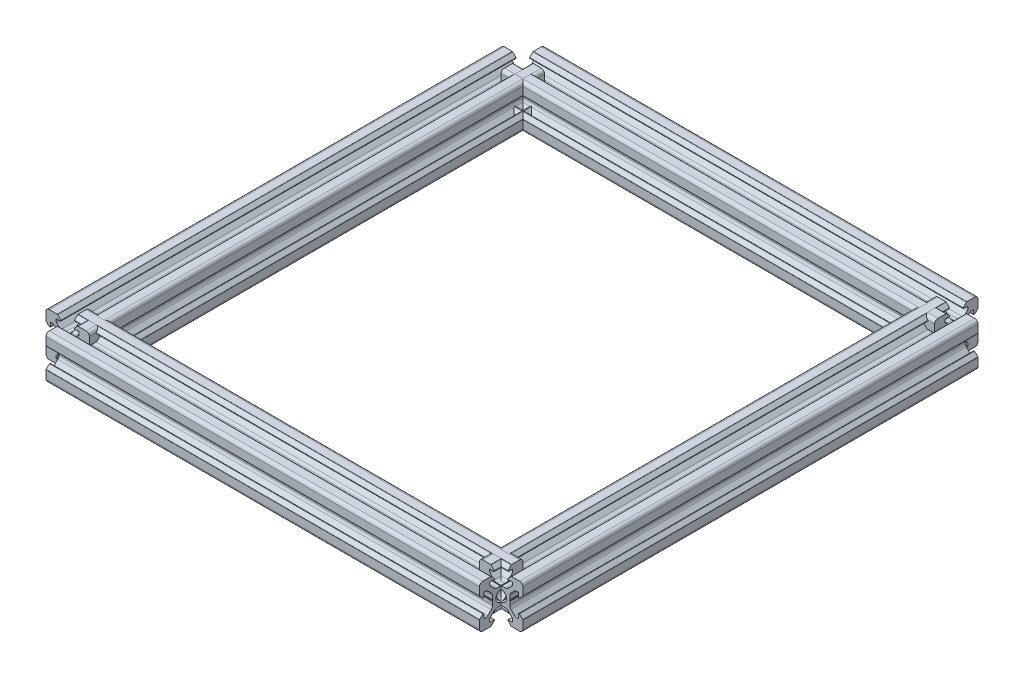
SolidWorks part; units mm, degrees
material "6061 Alloy"
ref_plane "Front Plane" through (0, 0, 0) normal (0, 0, 1) x (1, 0, 0)
ref_plane "Top Plane" through (0, 0, 0) normal (0, 1, 0) x (1, 0, 0)
ref_plane "Right Plane" through (0, 0, 0) normal (1, 0, 0) x (0, 0, -1)
sketch "Sketch1" plane through (0, 0, 0) normal (0, 1, 0) x (1, 0, 0)
  line L1 (-100, 105) -> (100, 105)
  line L2 (-100, 105) -> (-100, -105)
  line L3 (-100, -105) -> (100, -105)
  line L4 (100, 105) -> (100, -105)
  line L5 (-100, 105) -> (100, -105) construction
  line L6 (-100, -105) -> (100, 105) construction
  point P0 (0, 0)
  dimension "D1" = 200
  dimension "D2" = 210
other "Profile_20х20 20X20(1)"
ref_plane "Plane2" through (-100, 0, -105) normal (0, 0, 1) x (1, 0, 0)
sketch "Сечение" plane through (-100, 0, -105) normal (0, 0, 1) x (1, 0, 0)
  line L0 (-4, 1.8988) -> (-4, 0.3377)
  line L1 (-3.9452, 0.1815) -> (-3.8, 0)
  line L2 (-3.8, 0) -> (-3.9452, -0.1815)
  line L3 (-4, -0.3377) -> (-4, -1.8988)
  line L4 (-4.5858, -3.313) -> (-6.2799, -5.0071)
  line L5 (-6.987, -5.3) -> (-7.8, -5.3)
  line L6 (-8, -5.1) -> (-8, -3.33)
  line L7 (-8.4268, -3.1532) -> (-9.9268, -4.6532)
  line L8 (-10, -4.83) -> (-10, -8.5)
  line L9 (-8.5, -10) -> (-4.83, -10)
  line L10 (-4.6532, -9.9268) -> (-3.1532, -8.4268)
  line L11 (-3.33, -8) -> (-5.1, -8)
  line L12 (-5.3, -7.8) -> (-5.3, -6.987)
  line L13 (-5.0071, -6.2799) -> (-3.313, -4.5858)
  line L14 (-1.8988, -4) -> (-0.3377, -4)
  line L15 (-0.1815, -3.9452) -> (0, -3.8)
  line L16 (0, -3.8) -> (0.1815, -3.9452)
  line L17 (0.3377, -4) -> (1.8988, -4)
  line L18 (3.313, -4.5858) -> (5.0071, -6.2799)
  line L19 (5.3, -6.987) -> (5.3, -7.8)
  line L20 (5.1, -8) -> (3.33, -8)
  line L21 (3.1532, -8.4268) -> (4.6532, -9.9268)
  line L22 (4.83, -10) -> (8.5, -10)
  line L23 (10, -8.5) -> (10, -4.83)
  line L24 (9.9268, -4.6532) -> (8.4268, -3.1532)
  line L25 (8, -3.33) -> (8, -5.1)
  line L26 (7.8, -5.3) -> (6.987, -5.3)
  line L27 (6.2799, -5.0071) -> (4.5858, -3.313)
  line L28 (4, -1.8988) -> (4, -0.3377)
  line L29 (3.9452, -0.1815) -> (3.8, 0)
  line L30 (3.8, 0) -> (3.9452, 0.1815)
  line L31 (4, 0.3377) -> (4, 1.8988)
  line L32 (4.5858, 3.313) -> (6.2799, 5.0071)
  line L33 (6.987, 5.3) -> (7.8, 5.3)
  line L34 (8, 5.1) -> (8, 3.33)
  line L35 (8.4268, 3.1532) -> (9.9268, 4.6532)
  line L36 (10, 4.83) -> (10, 8.5)
  line L37 (8.5, 10) -> (4.83, 10)
  line L38 (4.6532, 9.9268) -> (3.1532, 8.4268)
  line L39 (3.33, 8) -> (5.1, 8)
  line L40 (5.3, 7.8) -> (5.3, 6.987)
  line L41 (5.0071, 6.2799) -> (3.313, 4.5858)
  line L42 (1.8988, 4) -> (0.3377, 4)
  line L43 (0.1815, 3.9452) -> (0, 3.8)
  line L44 (0, 3.8) -> (-0.1815, 3.9452)
  line L45 (-0.3377, 4) -> (-1.8988, 4)
  line L46 (-3.313, 4.5858) -> (-5.0071, 6.2799)
  line L47 (-5.3, 6.987) -> (-5.3, 7.8)
  line L48 (-5.1, 8) -> (-3.33, 8)
  line L49 (-3.1532, 8.4268) -> (-4.6532, 9.9268)
  line L50 (-4.83, 10) -> (-8.5, 10)
  line L51 (-10, 8.5) -> (-10, 4.83)
  line L52 (-9.9268, 4.6532) -> (-8.4268, 3.1532)
  line L53 (-8, 3.33) -> (-8, 5.1)
  line L54 (-7.8, 5.3) -> (-6.987, 5.3)
  line L55 (-6.2799, 5.0071) -> (-4.5858, 3.313)
  circle A0 centre (0, 0) radius 2.5
  arc A1 (-4, 0.3377) -> (-3.9452, 0.1815) centre (-3.75, 0.3377) ccw
  arc A2 (-3.9452, -0.1815) -> (-4, -0.3377) centre (-3.75, -0.3377) ccw
  arc A3 (-4, -1.8988) -> (-4.5858, -3.313) centre (-6, -1.8988) cw
  arc A4 (-6.2799, -5.0071) -> (-6.987, -5.3) centre (-6.987, -4.3) cw
  arc A5 (-7.8, -5.3) -> (-8, -5.1) centre (-7.8, -5.1) cw
  arc A6 (-8, -3.33) -> (-8.4268, -3.1532) centre (-8.25, -3.33) ccw
  arc A7 (-9.9268, -4.6532) -> (-10, -4.83) centre (-9.75, -4.83) ccw
  arc A8 (-10, -8.5) -> (-8.5, -10) centre (-8.5, -8.5) ccw
  arc A9 (-4.83, -10) -> (-4.6532, -9.9268) centre (-4.83, -9.75) ccw
  arc A10 (-3.1532, -8.4268) -> (-3.33, -8) centre (-3.33, -8.25) ccw
  arc A11 (-5.1, -8) -> (-5.3, -7.8) centre (-5.1, -7.8) cw
  arc A12 (-5.3, -6.987) -> (-5.0071, -6.2799) centre (-4.3, -6.987) cw
  arc A13 (-3.313, -4.5858) -> (-1.8988, -4) centre (-1.8988, -6) cw
  arc A14 (-0.3377, -4) -> (-0.1815, -3.9452) centre (-0.3377, -3.75) ccw
  arc A15 (0.1815, -3.9452) -> (0.3377, -4) centre (0.3377, -3.75) ccw
  arc A16 (1.8988, -4) -> (3.313, -4.5858) centre (1.8988, -6) cw
  arc A17 (5.0071, -6.2799) -> (5.3, -6.987) centre (4.3, -6.987) cw
  arc A18 (5.3, -7.8) -> (5.1, -8) centre (5.1, -7.8) cw
  arc A19 (3.33, -8) -> (3.1532, -8.4268) centre (3.33, -8.25) ccw
  arc A20 (4.6532, -9.9268) -> (4.83, -10) centre (4.83, -9.75) ccw
  arc A21 (8.5, -10) -> (10, -8.5) centre (8.5, -8.5) ccw
  arc A22 (10, -4.83) -> (9.9268, -4.6532) centre (9.75, -4.83) ccw
  arc A23 (8.4268, -3.1532) -> (8, -3.33) centre (8.25, -3.33) ccw
  arc A24 (8, -5.1) -> (7.8, -5.3) centre (7.8, -5.1) cw
  arc A25 (6.987, -5.3) -> (6.2799, -5.0071) centre (6.987, -4.3) cw
  arc A26 (4.5858, -3.313) -> (4, -1.8988) centre (6, -1.8988) cw
  arc A27 (4, -0.3377) -> (3.9452, -0.1815) centre (3.75, -0.3377) ccw
  arc A28 (3.9452, 0.1815) -> (4, 0.3377) centre (3.75, 0.3377) ccw
  arc A29 (4, 1.8988) -> (4.5858, 3.313) centre (6, 1.8988) cw
  arc A30 (6.2799, 5.0071) -> (6.987, 5.3) centre (6.987, 4.3) cw
  arc A31 (7.8, 5.3) -> (8, 5.1) centre (7.8, 5.1) cw
  arc A32 (8, 3.33) -> (8.4268, 3.1532) centre (8.25, 3.33) ccw
  arc A33 (9.9268, 4.6532) -> (10, 4.83) centre (9.75, 4.83) ccw
  arc A34 (10, 8.5) -> (8.5, 10) centre (8.5, 8.5) ccw
  arc A35 (4.83, 10) -> (4.6532, 9.9268) centre (4.83, 9.75) ccw
  arc A36 (3.1532, 8.4268) -> (3.33, 8) centre (3.33, 8.25) ccw
  arc A37 (5.1, 8) -> (5.3, 7.8) centre (5.1, 7.8) cw
  arc A38 (5.3, 6.987) -> (5.0071, 6.2799) centre (4.3, 6.987) cw
  arc A39 (3.313, 4.5858) -> (1.8988, 4) centre (1.8988, 6) cw
  arc A40 (0.3377, 4) -> (0.1815, 3.9452) centre (0.3377, 3.75) ccw
  arc A41 (-0.1815, 3.9452) -> (-0.3377, 4) centre (-0.3377, 3.75) ccw
  arc A42 (-1.8988, 4) -> (-3.313, 4.5858) centre (-1.8988, 6) cw
  arc A43 (-5.0071, 6.2799) -> (-5.3, 6.987) centre (-4.3, 6.987) cw
  arc A44 (-5.3, 7.8) -> (-5.1, 8) centre (-5.1, 7.8) cw
  arc A45 (-3.33, 8) -> (-3.1532, 8.4268) centre (-3.33, 8.25) ccw
  arc A46 (-4.6532, 9.9268) -> (-4.83, 10) centre (-4.83, 9.75) ccw
  arc A47 (-8.5, 10) -> (-10, 8.5) centre (-8.5, 8.5) ccw
  arc A48 (-10, 4.83) -> (-9.9268, 4.6532) centre (-9.75, 4.83) ccw
  arc A49 (-8.4268, 3.1532) -> (-8, 3.33) centre (-8.25, 3.33) ccw
  arc A50 (-8, 5.1) -> (-7.8, 5.3) centre (-7.8, 5.1) cw
  arc A51 (-6.987, 5.3) -> (-6.2799, 5.0071) centre (-6.987, 4.3) cw
  arc A52 (-4.5858, 3.313) -> (-4, 1.8988) centre (-6, 1.8988) cw
  point P162 (0, 0)
other "Profile_20х20 20X20(2)"
ref_plane "Plane4" through (-100, 0, 105) normal (1, 0, 0) x (0, 0, -1)
sketch "Сечение1" plane through (-100, 0, 105) normal (1, 0, 0) x (0, 0, -1)
  line L0 (-4, 1.8988) -> (-4, 0.3377)
  line L1 (-3.9452, 0.1815) -> (-3.8, 0)
  line L2 (-3.8, 0) -> (-3.9452, -0.1815)
  line L3 (-4, -0.3377) -> (-4, -1.8988)
  line L4 (-4.5858, -3.313) -> (-6.2799, -5.0071)
  line L5 (-6.987, -5.3) -> (-7.8, -5.3)
  line L6 (-8, -5.1) -> (-8, -3.33)
  line L7 (-8.4268, -3.1532) -> (-9.9268, -4.6532)
  line L8 (-10, -4.83) -> (-10, -8.5)
  line L9 (-8.5, -10) -> (-4.83, -10)
  line L10 (-4.6532, -9.9268) -> (-3.1532, -8.4268)
  line L11 (-3.33, -8) -> (-5.1, -8)
  line L12 (-5.3, -7.8) -> (-5.3, -6.987)
  line L13 (-5.0071, -6.2799) -> (-3.313, -4.5858)
  line L14 (-1.8988, -4) -> (-0.3377, -4)
  line L15 (-0.1815, -3.9452) -> (0, -3.8)
  line L16 (0, -3.8) -> (0.1815, -3.9452)
  line L17 (0.3377, -4) -> (1.8988, -4)
  line L18 (3.313, -4.5858) -> (5.0071, -6.2799)
  line L19 (5.3, -6.987) -> (5.3, -7.8)
  line L20 (5.1, -8) -> (3.33, -8)
  line L21 (3.1532, -8.4268) -> (4.6532, -9.9268)
  line L22 (4.83, -10) -> (8.5, -10)
  line L23 (10, -8.5) -> (10, -4.83)
  line L24 (9.9268, -4.6532) -> (8.4268, -3.1532)
  line L25 (8, -3.33) -> (8, -5.1)
  line L26 (7.8, -5.3) -> (6.987, -5.3)
  line L27 (6.2799, -5.0071) -> (4.5858, -3.313)
  line L28 (4, -1.8988) -> (4, -0.3377)
  line L29 (3.9452, -0.1815) -> (3.8, 0)
  line L30 (3.8, 0) -> (3.9452, 0.1815)
  line L31 (4, 0.3377) -> (4, 1.8988)
  line L32 (4.5858, 3.313) -> (6.2799, 5.0071)
  line L33 (6.987, 5.3) -> (7.8, 5.3)
  line L34 (8, 5.1) -> (8, 3.33)
  line L35 (8.4268, 3.1532) -> (9.9268, 4.6532)
  line L36 (10, 4.83) -> (10, 8.5)
  line L37 (8.5, 10) -> (4.83, 10)
  line L38 (4.6532, 9.9268) -> (3.1532, 8.4268)
  line L39 (3.33, 8) -> (5.1, 8)
  line L40 (5.3, 7.8) -> (5.3, 6.987)
  line L41 (5.0071, 6.2799) -> (3.313, 4.5858)
  line L42 (1.8988, 4) -> (0.3377, 4)
  line L43 (0.1815, 3.9452) -> (0, 3.8)
  line L44 (0, 3.8) -> (-0.1815, 3.9452)
  line L45 (-0.3377, 4) -> (-1.8988, 4)
  line L46 (-3.313, 4.5858) -> (-5.0071, 6.2799)
  line L47 (-5.3, 6.987) -> (-5.3, 7.8)
  line L48 (-5.1, 8) -> (-3.33, 8)
  line L49 (-3.1532, 8.4268) -> (-4.6532, 9.9268)
  line L50 (-4.83, 10) -> (-8.5, 10)
  line L51 (-10, 8.5) -> (-10, 4.83)
  line L52 (-9.9268, 4.6532) -> (-8.4268, 3.1532)
  line L53 (-8, 3.33) -> (-8, 5.1)
  line L54 (-7.8, 5.3) -> (-6.987, 5.3)
  line L55 (-6.2799, 5.0071) -> (-4.5858, 3.313)
  circle A0 centre (0, 0) radius 2.5
  arc A1 (-4, 0.3377) -> (-3.9452, 0.1815) centre (-3.75, 0.3377) ccw
  arc A2 (-3.9452, -0.1815) -> (-4, -0.3377) centre (-3.75, -0.3377) ccw
  arc A3 (-4, -1.8988) -> (-4.5858, -3.313) centre (-6, -1.8988) cw
  arc A4 (-6.2799, -5.0071) -> (-6.987, -5.3) centre (-6.987, -4.3) cw
  arc A5 (-7.8, -5.3) -> (-8, -5.1) centre (-7.8, -5.1) cw
  arc A6 (-8, -3.33) -> (-8.4268, -3.1532) centre (-8.25, -3.33) ccw
  arc A7 (-9.9268, -4.6532) -> (-10, -4.83) centre (-9.75, -4.83) ccw
  arc A8 (-10, -8.5) -> (-8.5, -10) centre (-8.5, -8.5) ccw
  arc A9 (-4.83, -10) -> (-4.6532, -9.9268) centre (-4.83, -9.75) ccw
  arc A10 (-3.1532, -8.4268) -> (-3.33, -8) centre (-3.33, -8.25) ccw
  arc A11 (-5.1, -8) -> (-5.3, -7.8) centre (-5.1, -7.8) cw
  arc A12 (-5.3, -6.987) -> (-5.0071, -6.2799) centre (-4.3, -6.987) cw
  arc A13 (-3.313, -4.5858) -> (-1.8988, -4) centre (-1.8988, -6) cw
  arc A14 (-0.3377, -4) -> (-0.1815, -3.9452) centre (-0.3377, -3.75) ccw
  arc A15 (0.1815, -3.9452) -> (0.3377, -4) centre (0.3377, -3.75) ccw
  arc A16 (1.8988, -4) -> (3.313, -4.5858) centre (1.8988, -6) cw
  arc A17 (5.0071, -6.2799) -> (5.3, -6.987) centre (4.3, -6.987) cw
  arc A18 (5.3, -7.8) -> (5.1, -8) centre (5.1, -7.8) cw
  arc A19 (3.33, -8) -> (3.1532, -8.4268) centre (3.33, -8.25) ccw
  arc A20 (4.6532, -9.9268) -> (4.83, -10) centre (4.83, -9.75) ccw
  arc A21 (8.5, -10) -> (10, -8.5) centre (8.5, -8.5) ccw
  arc A22 (10, -4.83) -> (9.9268, -4.6532) centre (9.75, -4.83) ccw
  arc A23 (8.4268, -3.1532) -> (8, -3.33) centre (8.25, -3.33) ccw
  arc A24 (8, -5.1) -> (7.8, -5.3) centre (7.8, -5.1) cw
  arc A25 (6.987, -5.3) -> (6.2799, -5.0071) centre (6.987, -4.3) cw
  arc A26 (4.5858, -3.313) -> (4, -1.8988) centre (6, -1.8988) cw
  arc A27 (4, -0.3377) -> (3.9452, -0.1815) centre (3.75, -0.3377) ccw
  arc A28 (3.9452, 0.1815) -> (4, 0.3377) centre (3.75, 0.3377) ccw
  arc A29 (4, 1.8988) -> (4.5858, 3.313) centre (6, 1.8988) cw
  arc A30 (6.2799, 5.0071) -> (6.987, 5.3) centre (6.987, 4.3) cw
  arc A31 (7.8, 5.3) -> (8, 5.1) centre (7.8, 5.1) cw
  arc A32 (8, 3.33) -> (8.4268, 3.1532) centre (8.25, 3.33) ccw
  arc A33 (9.9268, 4.6532) -> (10, 4.83) centre (9.75, 4.83) ccw
  arc A34 (10, 8.5) -> (8.5, 10) centre (8.5, 8.5) ccw
  arc A35 (4.83, 10) -> (4.6532, 9.9268) centre (4.83, 9.75) ccw
  arc A36 (3.1532, 8.4268) -> (3.33, 8) centre (3.33, 8.25) ccw
  arc A37 (5.1, 8) -> (5.3, 7.8) centre (5.1, 7.8) cw
  arc A38 (5.3, 6.987) -> (5.0071, 6.2799) centre (4.3, 6.987) cw
  arc A39 (3.313, 4.5858) -> (1.8988, 4) centre (1.8988, 6) cw
  arc A40 (0.3377, 4) -> (0.1815, 3.9452) centre (0.3377, 3.75) ccw
  arc A41 (-0.1815, 3.9452) -> (-0.3377, 4) centre (-0.3377, 3.75) ccw
  arc A42 (-1.8988, 4) -> (-3.313, 4.5858) centre (-1.8988, 6) cw
  arc A43 (-5.0071, 6.2799) -> (-5.3, 6.987) centre (-4.3, 6.987) cw
  arc A44 (-5.3, 7.8) -> (-5.1, 8) centre (-5.1, 7.8) cw
  arc A45 (-3.33, 8) -> (-3.1532, 8.4268) centre (-3.33, 8.25) ccw
  arc A46 (-4.6532, 9.9268) -> (-4.83, 10) centre (-4.83, 9.75) ccw
  arc A47 (-8.5, 10) -> (-10, 8.5) centre (-8.5, 8.5) ccw
  arc A48 (-10, 4.83) -> (-9.9268, 4.6532) centre (-9.75, 4.83) ccw
  arc A49 (-8.4268, 3.1532) -> (-8, 3.33) centre (-8.25, 3.33) ccw
  arc A50 (-8, 5.1) -> (-7.8, 5.3) centre (-7.8, 5.1) cw
  arc A51 (-6.987, 5.3) -> (-6.2799, 5.0071) centre (-6.987, 4.3) cw
  arc A52 (-4.5858, 3.313) -> (-4, 1.8988) centre (-6, 1.8988) cw
  point P162 (0, 0)
